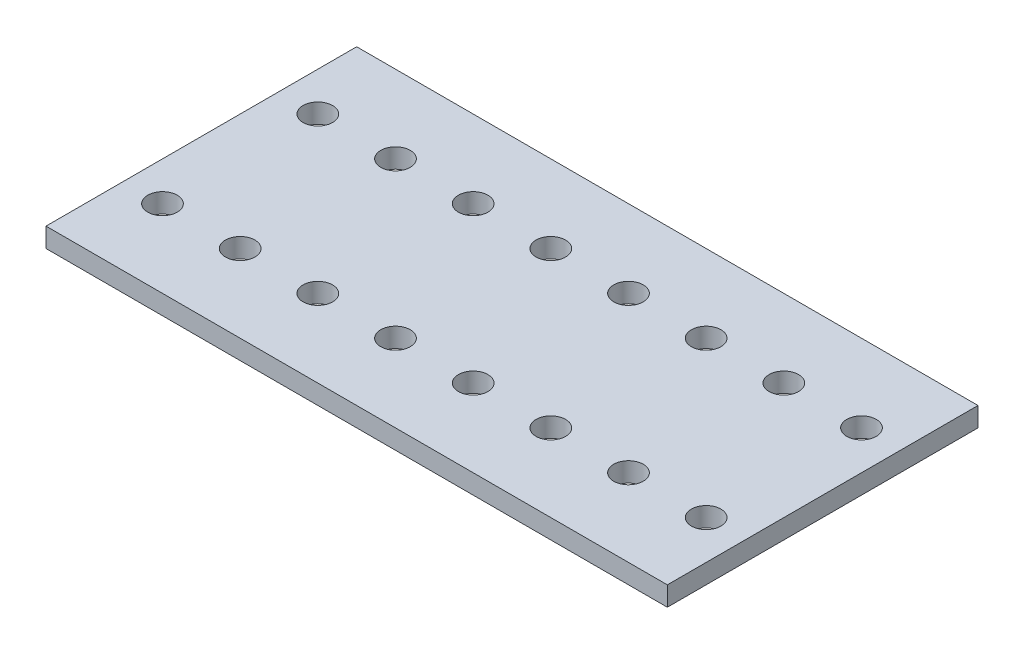
SolidWorks part; units mm, degrees
ref_plane "Front Plane" through (0, 0, 0) normal (0, 0, 1) x (1, 0, 0)
ref_plane "Top Plane" through (0, 0, 0) normal (0, 1, 0) x (1, 0, 0)
ref_plane "Right Plane" through (0, 0, 0) normal (1, 0, 0) x (0, 0, -1)
sketch "Sketch1" plane through (0, 0, 0) normal (0, 1, 0) x (1, 0, 0)
  line L1 (0, 0) -> (101.6, 0)
  line L2 (0, 0) -> (0, 50.8)
  line L3 (0, 50.8) -> (101.6, 50.8)
  line L4 (101.6, 0) -> (101.6, 50.8)
  dimension "D1" = 50.8
  dimension "D2" = 101.6
extrude "Boss-Extrude1" add sketch "Sketch1" along normal blind 3.175
sketch "Sketch2" plane through (0, 3.175, 0) normal (0, 1, 0) x (1, 0, 0)
  line L0 (101.6, 50.8) -> (0, 50.8) construction
  line L1 (0, 50.8) -> (0, 0) construction
  line L2 (0, 0) -> (101.6, 0) construction
  circle A0 centre (6.35, 38.1) radius 2.413
  circle A1 centre (6.35, 12.7) radius 2.413
  circle A2 centre (19.05, 38.1) radius 2.413
  circle A3 centre (19.05, 12.7) radius 2.413
  circle A4 centre (31.75, 38.1) radius 2.413
  circle A5 centre (31.75, 12.7) radius 2.413
  circle A6 centre (44.45, 38.1) radius 2.413
  circle A7 centre (44.45, 12.7) radius 2.413
  circle A8 centre (57.15, 38.1) radius 2.413
  circle A9 centre (57.15, 12.7) radius 2.413
  circle A10 centre (69.85, 38.1) radius 2.413
  circle A11 centre (69.85, 12.7) radius 2.413
  circle A12 centre (82.55, 38.1) radius 2.413
  circle A13 centre (82.55, 12.7) radius 2.413
  circle A14 centre (95.25, 38.1) radius 2.413
  circle A15 centre (95.25, 12.7) radius 2.413
  dimension "D1" = 12.7
  dimension "D2" = 6.35
  dimension "D3" = 4.826
  dimension "D4" = 4.826
  dimension "D5" = 12.7
  dimension "D6" = 6.35
  dimension "D7" = 8
extrude "Cut-Extrude1" cut sketch "Sketch2" against normal through all
